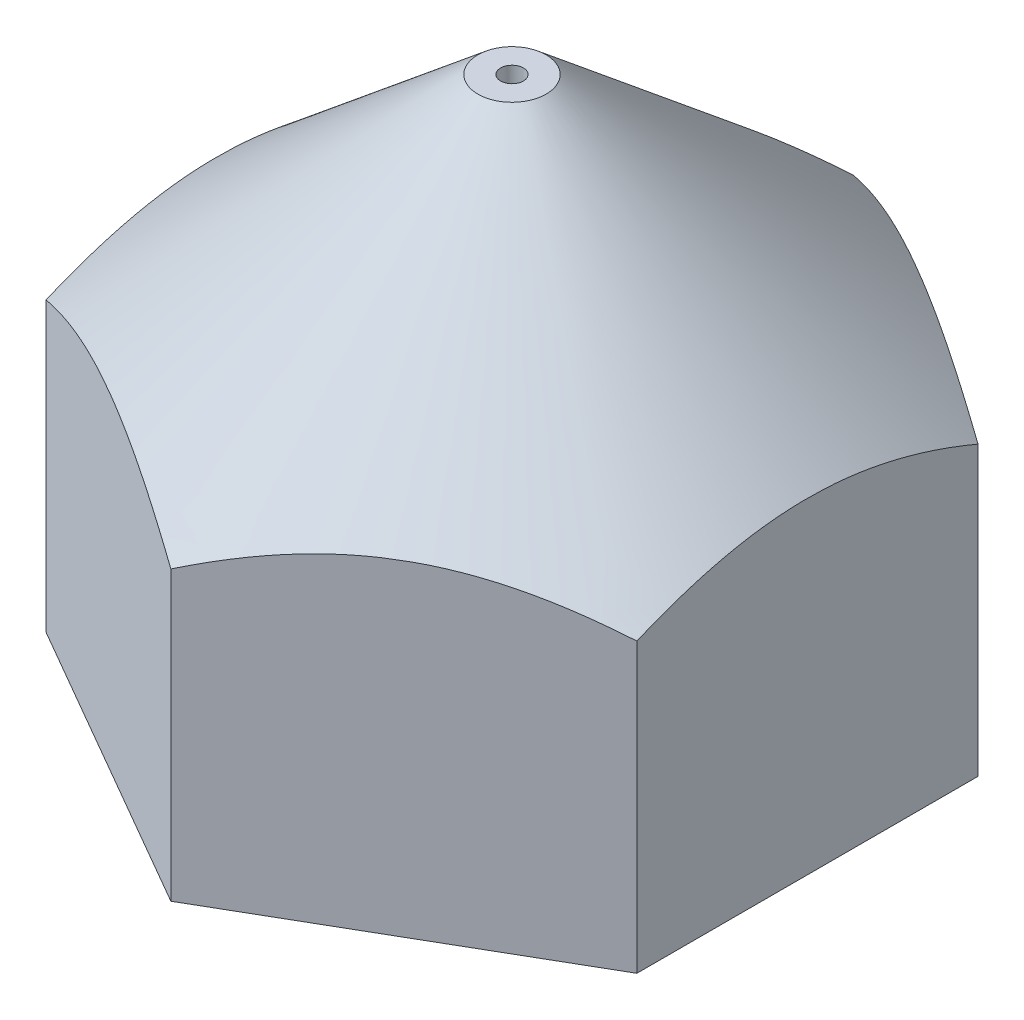
SolidWorks part; units mm, degrees
material "6061 Alloy"
ref_plane "Front Plane" through (0, 0, 0) normal (0, 0, 1) x (1, 0, 0)
ref_plane "Top Plane" through (0, 0, 0) normal (0, 1, 0) x (1, 0, 0)
ref_plane "Right Plane" through (0, 0, 0) normal (1, 0, 0) x (0, 0, -1)
sketch "Sketch1" plane through (0, 0, 0) normal (0, 1, 0) x (1, 0, 0)
  line L1 (0, 7.5056) -> (-6.5, 3.7528)
  line L2 (-6.5, 3.7528) -> (-6.5, -3.7528)
  line L3 (-6.5, -3.7528) -> (0, -7.5056)
  line L4 (0, -7.5056) -> (6.5, -3.7528)
  line L5 (6.5, -3.7528) -> (6.5, 3.7528)
  line L6 (6.5, 3.7528) -> (0, 7.5056)
  circle A0 centre (0, 0) radius 6.5 construction
  dimension "D1" = 13
extrude "Boss-Extrude1" add sketch "Sketch1" along normal mid plane 12
sketch "Sketch2" plane through (0, 0, 0) normal (-1, 0, 0) x (0, 0, 1)
  line L0 (-0.75, 6) -> (-7.5056, 0.3314)
  line L3 (-3.7528, 6) -> (3.7528, 6) construction
  line L4 (-7.5056, 6) -> (-7.5056, -6) construction
  line L5 (0, 0) -> (0, 6.656) construction
  line L6 (-0.75, 6) -> (-7.5056, 6)
  line L7 (-7.5056, 6) -> (-7.5056, 0.3314)
  dimension "D1" = 40
  dimension "D2" = 1.5
revolve "Cut-Revolve3" cut sketch "Sketch2" angle 360 about L5
sketch "Sketch3" plane through (0, 6, 0) normal (0, 1, 0) x (1, 0, 0)
  circle A0 centre (0, 0) radius 0.25
  dimension "D1" = 0.5
extrude "Cut-Extrude1" cut sketch "Sketch3" against normal through all
sketch "Sketch4" plane through (0, 0, 0) normal (1, 0, 0) x (0, 0, -1)
  line L0 (0, 6) -> (0, -6) construction
  line L1 (0.75, 6) -> (-0.75, 6) construction
  line L2 (-3.7528, -6) -> (3.7528, -6) construction
  line L3 (0, -6) -> (-5, -6)
  line L4 (-7.5056, -6) -> (-3.7528, -6) construction
  line L5 (-5, -6) -> (-5, 0)
  line L6 (-5, 0) -> (-1.8375, 0)
  line L7 (-1.8375, 0) -> (-1.5875, 0.25)
  line L8 (-1.5875, 0.25) -> (-1.5875, 3.2328)
  line L9 (-1.5875, 3.2328) -> (0, 5.5)
  line L10 (0, 5.5) -> (0, -6)
  dimension "D1" = 55
  dimension "D2" = 0.5
  dimension "D3" = 6
  dimension "D4" = 10
  dimension "D5" = 3.175
  dimension "D6" = 45
  dimension "D7" = 0.25
revolve "Cut-Revolve4" cut sketch "Sketch4" angle 360 about L0
